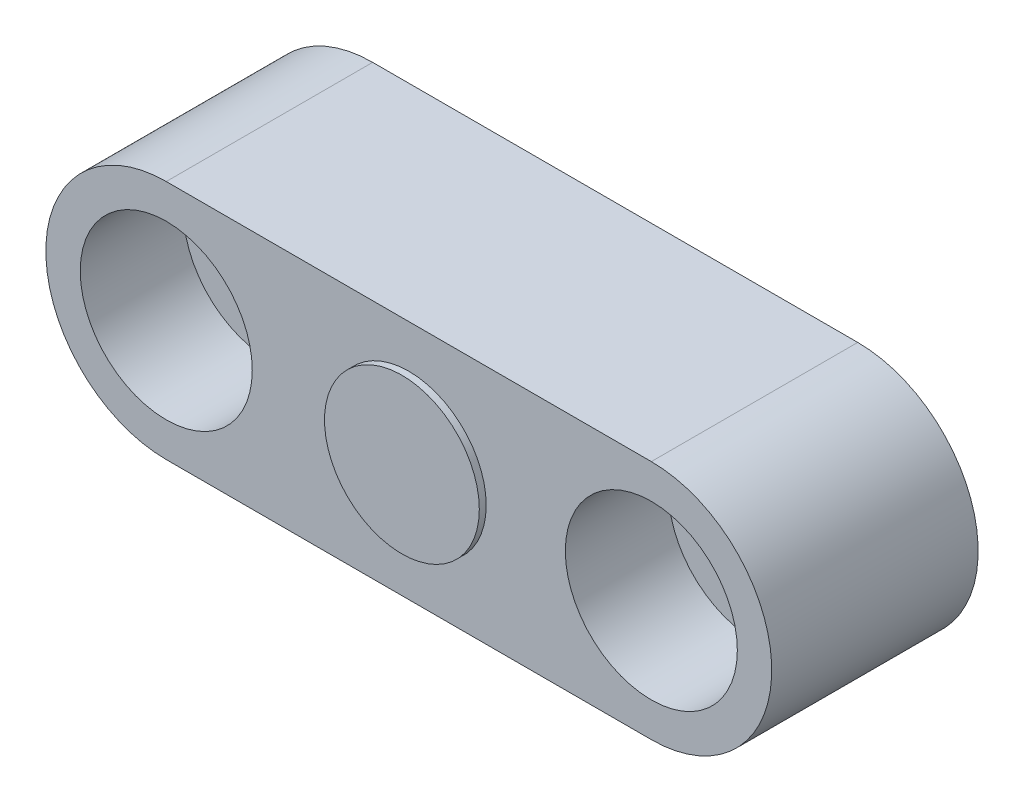
SolidWorks part; units mm, degrees
material "ABS PC"
ref_plane "Piano frontale" through (0, 0, 0) normal (0, 0, 1) x (1, 0, 0)
ref_plane "Piano superiore" through (0, 0, 0) normal (0, 1, 0) x (1, 0, 0)
ref_plane "Piano destro" through (0, 0, 0) normal (1, 0, 0) x (0, 0, -1)
sketch "Schizzo1" plane through (0, 0, 0) normal (0, 0, 1) x (1, 0, 0)
  line L0 (-7.05, 0) -> (7.05, 0) construction
  line L4 (7.05, -3.5) -> (-7.05, -3.5)
  line L7 (-7.05, 3.5) -> (7.05, 3.5)
  arc A2 (-7.05, 3.5) -> (-7.05, -3.5) centre (-7.05, 0) ccw
  arc A7 (7.05, 3.5) -> (7.05, -3.5) centre (7.05, 0) cw
  point P2 (0, 0)
  point P4 (0, 0)
  point P12 (0, 0)
  dimension "D3" = 7
  dimension "D1" = 14.1
extrude "Estrusione-Estrusione1" add sketch "Schizzo1" along normal blind 6
sketch "Schizzo2" plane through (0, 0, 6) normal (0, 0, 1) x (1, 0, 0)
  line L0 (-15.6186, 0) -> (15.6186, 0) construction
  line L1 (0, -7.8679) -> (0, 7.8679) construction
  circle A0 centre (7.05, 0) radius 2.5
  point P0 (7.2195, 0)
  point P3 (8.7276, 0)
  point P4 (0, 0)
  point P8 (0, 0)
  dimension "D1" = 5
extrude "Taglio-Estrusione1" cut sketch "Schizzo2" against normal blind 3
sketch "Schizzo3" plane through (0, 0, 3) normal (0, 0, 1) x (1, 0, 0)
  circle A0 centre (7.05, 0) radius 1.75
  dimension "D1" = 3.5
extrude "Taglio-Estrusione2" cut sketch "Schizzo3" against normal through all
sketch "Schizzo4" plane through (0, 0, 0) normal (0, 0, -1) x (-1, 0, 0)
  circle A2 centre (-7.05, 0) radius 2.5
  circle A3 centre (-7.05, 0) radius 2.5
  circle A5 centre (-7.05, 0) radius 1.75 construction
  circle A6 centre (-7.05, 0) radius 1.75
  point P1 (-7.2195, 0)
  point P2 (0, 0)
  dimension "D1" = 0
extrude "Taglio-Estrusione3" cut sketch "Schizzo4" against normal blind 2
mirror "Specchia1" about plane through (0, 0, 0) normal (1, 0, 0) of "Taglio-Estrusione3", "Taglio-Estrusione2", "Taglio-Estrusione1"
sketch "Schizzo6" plane through (0, 0, 0) normal (0, 0, -1) x (-1, 0, 0)
  line L0 (-5.4579, 2.75) -> (5.4579, 2.75)
  line L1 (-5.4579, -2.75) -> (5.4579, -2.75)
  line L2 (-7.05, 3.5) -> (7.05, 3.5) construction
  line L3 (0, 3.3) -> (0, -3.3) construction
  line L4 (7.05, -3.5) -> (-7.05, -3.5) construction
  circle A0 centre (-7.05, 0) radius 2.5 construction
  arc A4 (-5.4579, 2.75) -> (-5.4579, -2.75) centre (-7.05, 0) cw
  arc A6 (5.4579, 2.75) -> (5.4579, -2.75) centre (7.05, 0) ccw
  point P9 (0, 0)
  point P17 (0, 0)
  dimension "D3" = 3.1776
  dimension "D1" = 0.75
  dimension "D2" = 0.75
extrude "Taglio-Estrusione4" cut sketch "Schizzo6" against normal offset from surface (5 mm away) 1 up to face at (-9.55, 0, 6)
sketch "Schizzo5" plane through (0, 0, 6) normal (0, 0, 1) x (1, 0, 0)
  circle A0 centre (0, 0) radius 2.25
  dimension "D1" = 4.5
extrude "Estrusione-Estrusione2" add sketch "Schizzo5" along normal blind 0.2 and the other way blind 1.2
